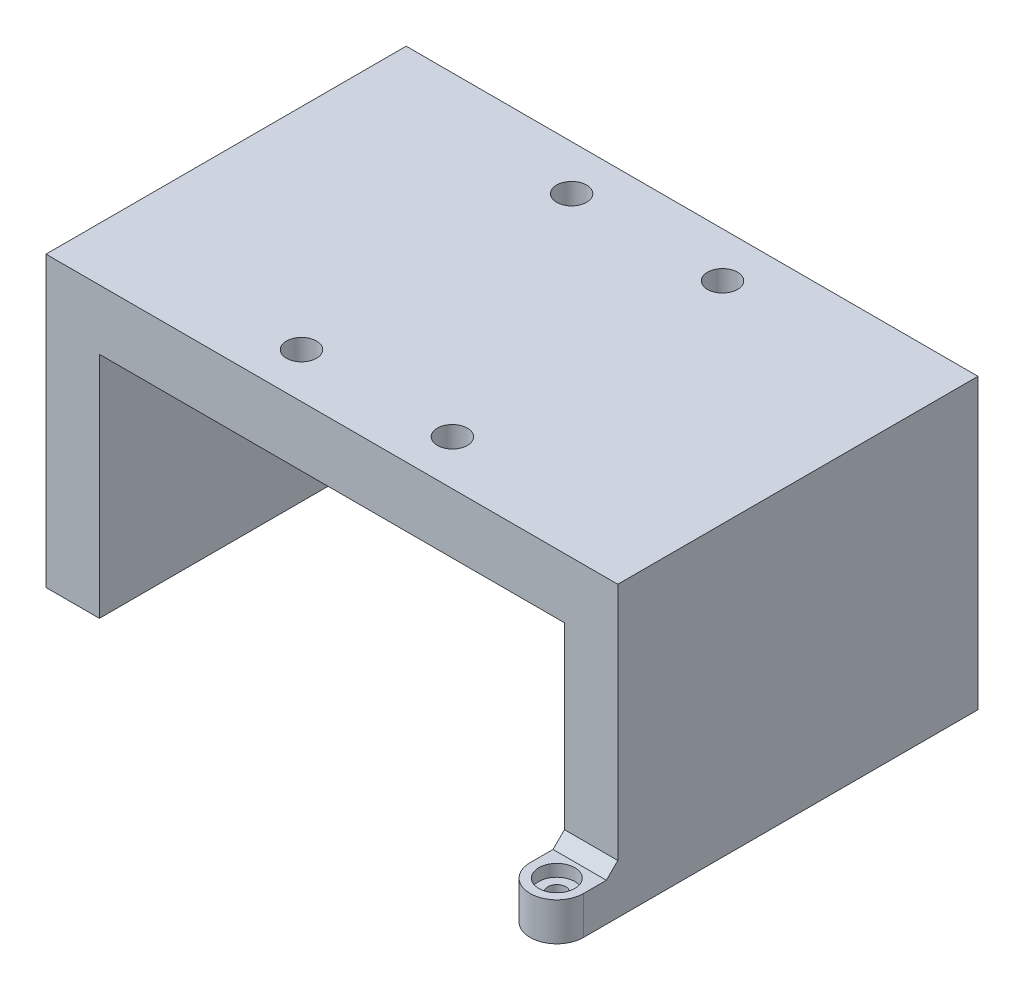
SolidWorks part; units mm, degrees
ref_plane "Front Plane" through (0, 0, 0) normal (0, 0, 1) x (1, 0, 0)
ref_plane "Top Plane" through (0, 0, 0) normal (0, 1, 0) x (1, 0, 0)
ref_plane "Right Plane" through (0, 0, 0) normal (1, 0, 0) x (0, 0, -1)
sketch "Sketch2" plane through (0, 0, 0) normal (0, 1, 0) x (1, 0, 0)
  line L0 (-12.57, 22.5) -> (12.57, 22.5) construction
  line L1 (-47.625, -30) -> (47.625, -30)
  line L2 (-47.625, -30) -> (-47.625, 30)
  line L3 (-47.625, 30) -> (47.625, 30)
  line L4 (47.625, -30) -> (47.625, 30)
  line L5 (-47.625, -30) -> (47.625, 30) construction
  line L6 (-47.625, 30) -> (47.625, -30) construction
  line L7 (-12.57, 22.5) -> (-12.57, -22.5) construction
  line L8 (-12.57, -22.5) -> (12.57, -22.5) construction
  line L9 (12.57, 22.5) -> (12.57, -22.5) construction
  line L10 (0, 22.5) -> (0, -22.5) construction
  line L11 (-12.57, 0) -> (12.57, 0) construction
  circle A0 centre (12.57, 22.5) radius 2.5
  circle A1 centre (-12.57, 22.5) radius 2.5
  circle A2 centre (12.57, -22.5) radius 2.5
  circle A4 centre (-12.57, -22.5) radius 2.5
  point P0 (0, 0)
  point P14 (0, 0)
  dimension "D5" = 5
  dimension "D1" = 95.25
  dimension "D2" = 60
  dimension "D3" = 25.14
  dimension "D4" = 45
extrude "Boss-Extrude1" add sketch "Sketch2" along normal blind 10
sketch "Sketch4" plane through (0, 0, 0) normal (0, -1, 0) x (1, 0, 0)
  line L0 (47.625, -30) -> (-47.625, -30) construction
  line L1 (-47.625, 30) -> (-38.735, 30)
  line L2 (-47.625, 30) -> (-47.625, -30)
  line L3 (-47.625, -30) -> (-38.735, -30)
  line L4 (-38.735, 30) -> (-38.735, -30)
  line L6 (47.625, 30) -> (38.735, 30)
  line L7 (47.625, 30) -> (47.625, -30)
  line L8 (47.625, -30) -> (38.735, -30)
  line L9 (38.735, 30) -> (38.735, -30)
  dimension "D1" = 8.89
  dimension "D2" = 8.89
extrude "Boss-Extrude2" add sketch "Sketch4" along normal blind 38.1
sketch "Sketch6" plane through (0, -38.1, 0) normal (0, -1, 0) x (1, 0, 0)
  line L0 (47.625, 0) -> (-47.625, 0) construction
  line L1 (-47.625, 30) -> (-47.625, -30) construction
  line L2 (-47.625, -4.445) -> (-53.34, -4.445)
  line L3 (-53.34, 4.445) -> (-47.625, 4.445)
  line L4 (-47.625, -4.445) -> (-47.625, 4.445)
  line L5 (0, -55) -> (0, 55) construction
  line L6 (47.625, -4.445) -> (47.625, 4.445) construction
  line L7 (53.34, 4.445) -> (47.625, 4.445) construction
  line L8 (47.625, -4.445) -> (53.34, -4.445) construction
  line L9 (38.735, 30) -> (38.735, 35.715)
  line L10 (47.625, 35.715) -> (47.625, 30)
  line L11 (47.625, 30) -> (38.735, 30)
  arc A0 (-53.34, -4.445) -> (-53.34, 4.445) centre (-53.34, 0) cw
  circle A1 centre (-53.34, 0) radius 1.5
  circle A2 centre (53.34, 0) radius 1.5 construction
  arc A3 (53.34, -4.445) -> (53.34, 4.445) centre (53.34, 0) ccw construction
  arc A4 (38.735, 35.715) -> (47.625, 35.715) centre (43.18, 35.715) cw
  circle A5 centre (43.18, 35.715) radius 1.5
  point P14 (0, 0)
  dimension "D3" = 3
  dimension "D2" = 10.16
  dimension "D5" = 10.16
  dimension "D6" = 3
  dimension "D1" = 8.89
  dimension "D4" = 106.68
extrude "Boss-Extrude3" add sketch "Sketch6" against normal blind 6.35
sketch "Sketch8" plane through (0, -31.75, 0) normal (0, 1, 0) x (1, 0, 0)
  circle A0 centre (43.18, -35.715) radius 2.9997
  circle A1 centre (-53.34, 0) radius 2.9997
  circle A2 centre (43.18, -35.715) radius 1.5 construction
  dimension "D1" = 5.9995
extrude "Cut-Extrude2" cut sketch "Sketch8" against normal blind 1.999
chamfer "Chamfer2" distance 1.905 angle 45 2 edges at (-47.625, -31.75, 0) (43.18, -31.75, 30)
